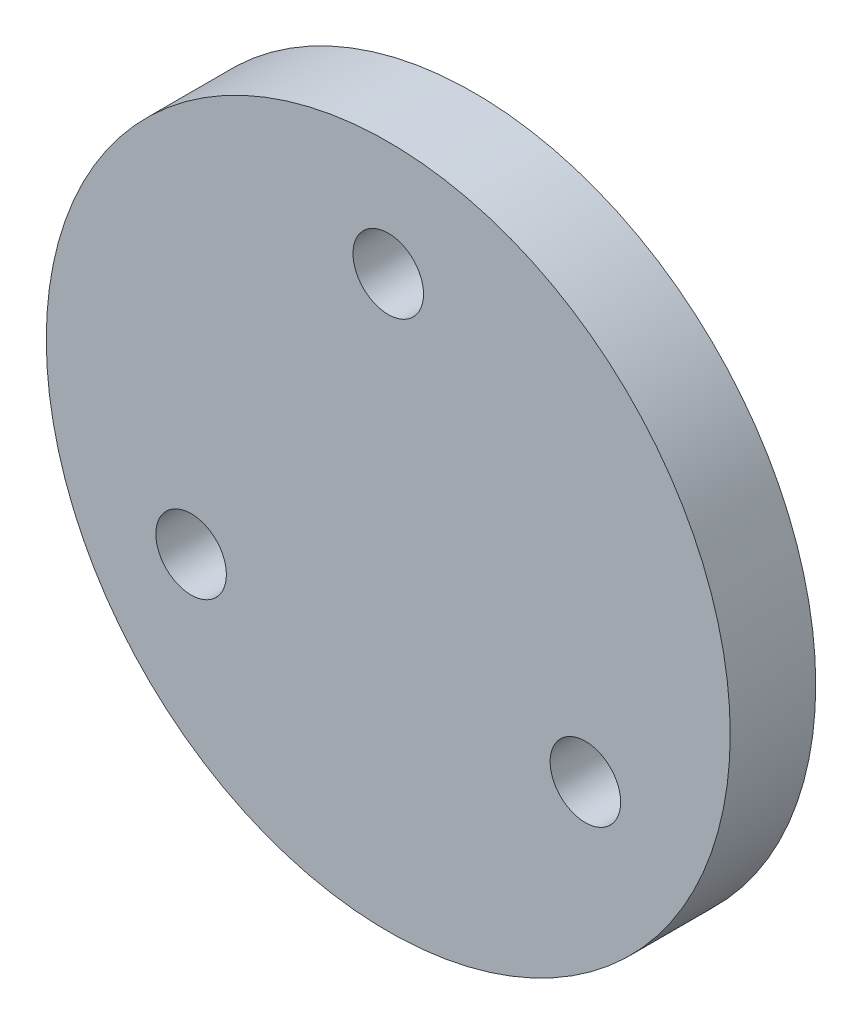
SolidWorks part; units mm, degrees
ref_plane "Front Plane" through (0, 0, 0) normal (0, 0, 1) x (1, 0, 0)
ref_plane "Top Plane" through (0, 0, 0) normal (0, 1, 0) x (1, 0, 0)
ref_plane "Right Plane" through (0, 0, 0) normal (1, 0, 0) x (0, 0, -1)
sketch "Sketch1" plane through (0, 0, 0) normal (0, 0, 1) x (1, 0, 0)
  line L0 (0, 16) -> (0, 0) construction
  line L1 (0, 0) -> (-13.8564, -8) construction
  line L2 (0, 0) -> (13.8564, -8) construction
  circle A0 centre (0, 0) radius 16
  circle A1 centre (0, 0) radius 9 construction
  circle A2 centre (9.2232, -5.325) radius 1.65
  circle A3 centre (0, 10.65) radius 1.65
  circle A4 centre (-9.2232, -5.325) radius 1.65
  dimension "D1" = 32
  dimension "D2" = 18
  dimension "D5" = 3.3
  dimension "D3" = 120
  dimension "D4" = 120
extrude "Boss-Extrude1" add sketch "Sketch1" along normal blind 4
